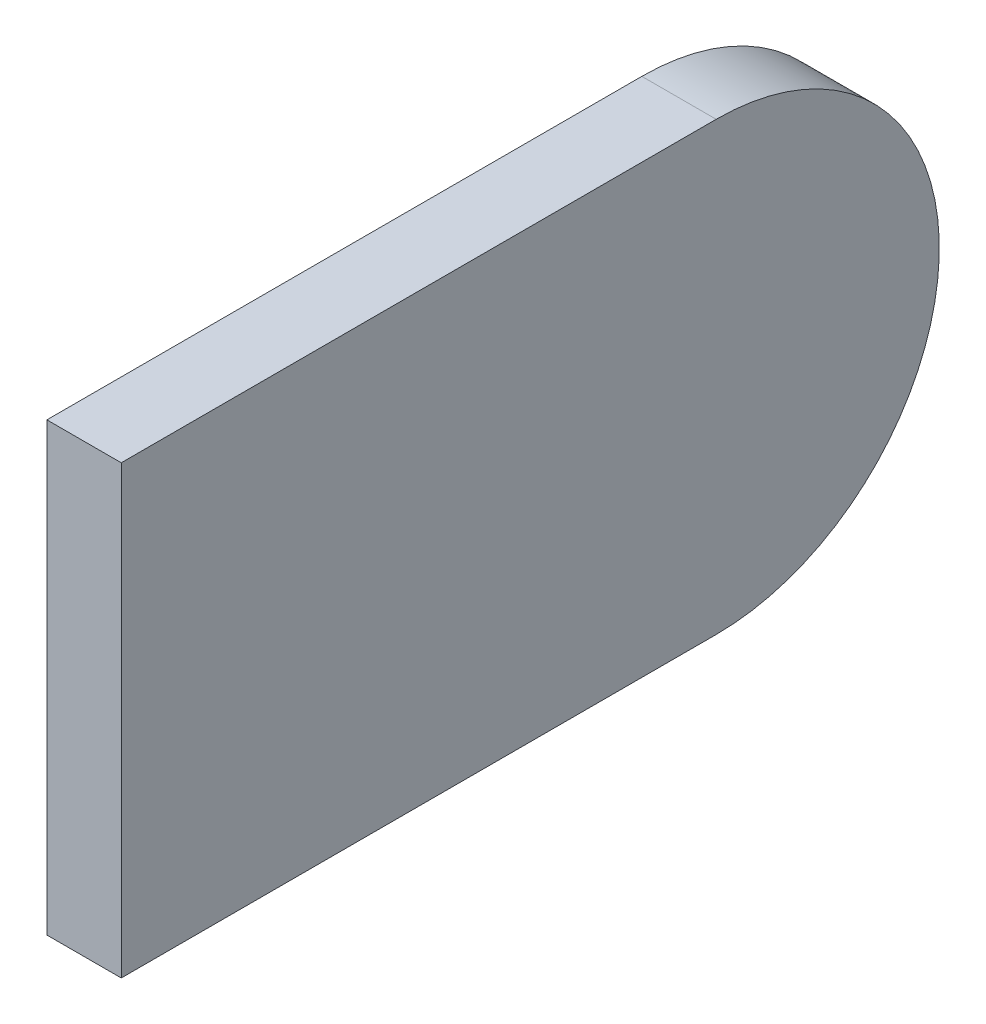
SolidWorks part; units mm, degrees
material "Plain Carbon Steel"
ref_plane "Front Plane" through (0, 0, 0) normal (0, 0, 1) x (1, 0, 0)
ref_plane "Top Plane" through (0, 0, 0) normal (0, 1, 0) x (1, 0, 0)
ref_plane "Right Plane" through (0, 0, 0) normal (1, 0, 0) x (0, 0, -1)
sketch "Sketch1" plane through (0, 0, 0) normal (1, 0, 0) x (0, 0, -1)
  line L0 (0, 0) -> (0, 60)
  line L1 (0, 60) -> (80, 60)
  line L2 (80, 0) -> (0, 0)
  arc A0 (80, 60) -> (80, 0) centre (80, 30) cw
  dimension "D2" = 30
  dimension "D1" = 80
extrude "Boss-Extrude1" add sketch "Sketch1" along normal blind 10
